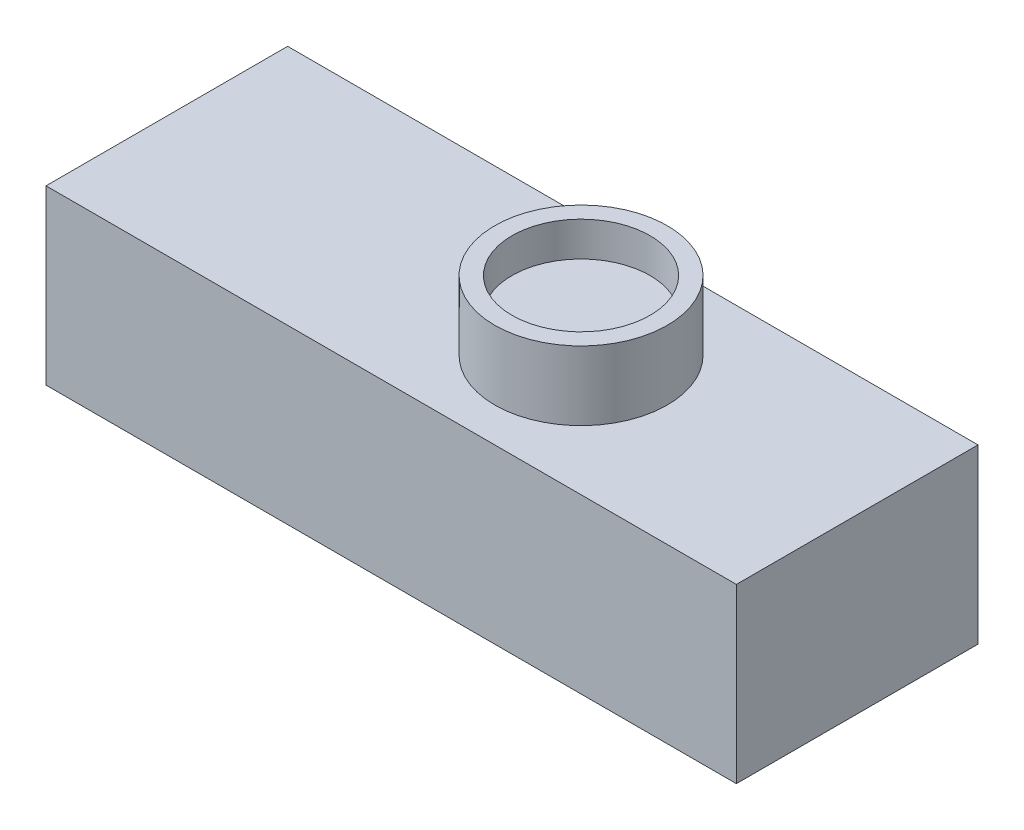
SolidWorks part; units mm, degrees
ref_plane "Front Plane" through (0, 0, 0) normal (0, 0, 1) x (1, 0, 0)
ref_plane "Top Plane" through (0, 0, 0) normal (0, 1, 0) x (1, 0, 0)
ref_plane "Right Plane" through (0, 0, 0) normal (1, 0, 0) x (0, 0, -1)
sketch "Sketch1" plane through (0, 0, 0) normal (0, 1, 0) x (1, 0, 0)
  line L1 (10, -3.5) -> (-10, -3.5)
  line L2 (10, -3.5) -> (10, 3.5)
  line L3 (10, 3.5) -> (-10, 3.5)
  line L4 (-10, -3.5) -> (-10, 3.5)
  line L5 (10, -3.5) -> (-10, 3.5) construction
  line L6 (10, 3.5) -> (-10, -3.5) construction
  point P0 (0, 0)
  dimension "D1" = 20
  dimension "D2" = 7
extrude "Boss-Extrude1" add sketch "Sketch1" along normal blind 5
sketch "Sketch2" plane through (0, 5, 0) normal (0, 1, 0) x (1, 0, 0)
  line L0 (0, 0) -> (2, 0) construction
  circle A0 centre (2, 0) radius 2.5
  dimension "D1" = 5
  dimension "D2" = 2
extrude "Boss-Extrude2" add sketch "Sketch2" along normal blind 2
sketch "Sketch3" plane through (0, 7, 0) normal (0, 1, 0) x (1, 0, 0)
  circle A0 centre (2, 0) radius 2
  dimension "D1" = 4
extrude "Cut-Extrude1" cut sketch "Sketch3" against normal blind 1
